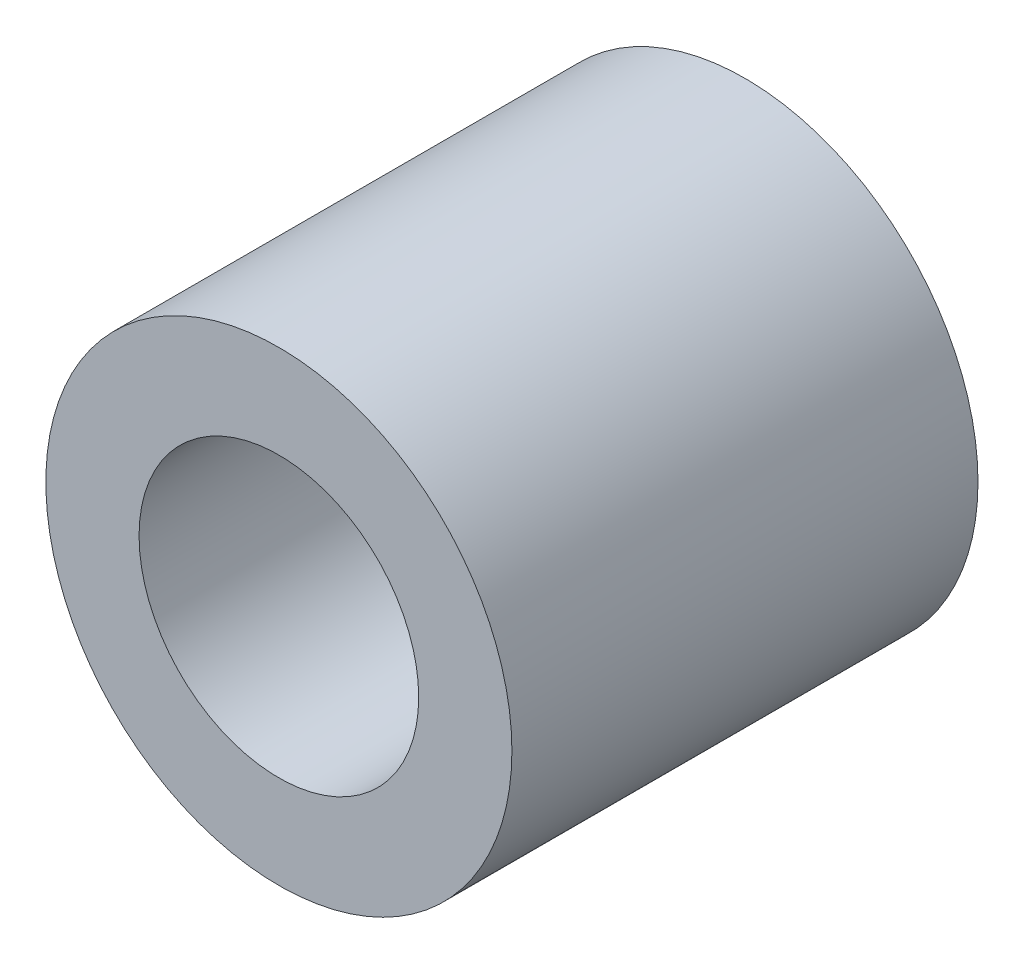
SolidWorks part; units mm, degrees
ref_plane "Front Plane" through (0, 0, 0) normal (0, 0, 1) x (1, 0, 0)
ref_plane "Top Plane" through (0, 0, 0) normal (0, 1, 0) x (1, 0, 0)
ref_plane "Right Plane" through (0, 0, 0) normal (1, 0, 0) x (0, 0, -1)
sketch "Sketch2" plane through (0, 0, 0) normal (0, 0, 1) x (1, 0, 0)
  circle A0 centre (0, 0) radius 5
extrude "Boss-Extrude1" add sketch "Sketch2" along normal blind 10
sketch "Sketch3" plane through (0, 0, 0) normal (0, 0, -1) x (-1, 0, 0)
  circle A0 centre (0, 0) radius 3
extrude "Cut-Extrude1" cut sketch "Sketch3" against normal blind 10
